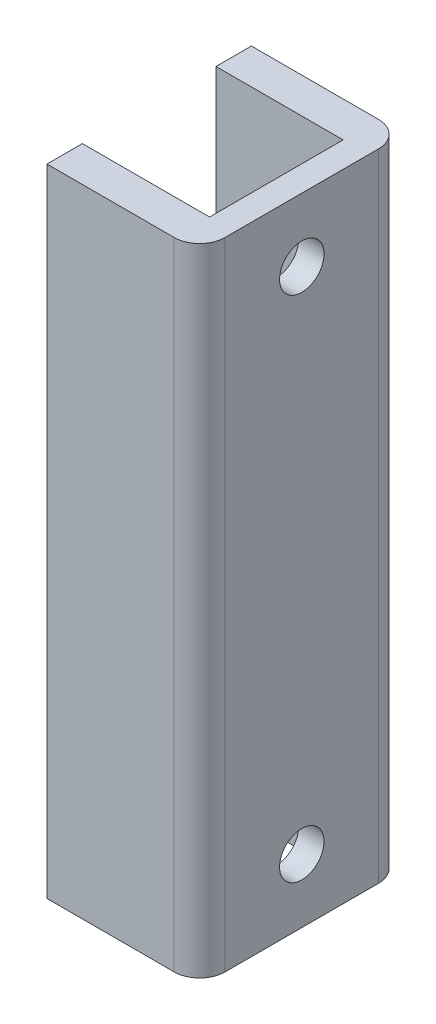
SolidWorks part; units mm, degrees
ref_plane "前视基准面" through (0, 0, 0) normal (0, 0, 1) x (1, 0, 0)
ref_plane "上视基准面" through (0, 0, 0) normal (0, 1, 0) x (1, 0, 0)
ref_plane "右视基准面" through (0, 0, 0) normal (1, 0, 0) x (0, 0, -1)
sketch "草图1" plane through (0, 0, 0) normal (0, 1, 0) x (1, 0, 0)
  line L0 (-8.0532, 9.2928) -> (1.9468, 9.2928)
  line L1 (3.9468, 7.2928) -> (3.9468, -4.7772)
  line L2 (1.9468, -6.7772) -> (-8.0532, -6.7772)
  line L3 (-8.0532, -6.7772) -> (-8.0532, -3.9922)
  line L4 (-8.0532, -3.9922) -> (1.9468, -3.9922)
  line L5 (1.9468, -3.9922) -> (1.9468, 6.5078)
  line L6 (1.9468, 6.5078) -> (-8.0532, 6.5078)
  line L7 (-8.0532, 6.5078) -> (-8.0532, 9.2928)
  arc A0 (3.9468, -4.7772) -> (1.9468, -6.7772) centre (1.9468, -4.7772) cw
  arc A1 (1.9468, 9.2928) -> (3.9468, 7.2928) centre (1.9468, 7.2928) cw
  point P10 (3.9468, -6.7772)
  point P13 (3.9468, 9.2928)
  dimension "D7" = 2
  dimension "D1" = 16.07
  dimension "D2" = 12
  dimension "D3" = 12
  dimension "D4" = 2.785
  dimension "D5" = 10.5
  dimension "D6" = 2
extrude "凸台-拉伸1" add sketch "草图1" along normal blind 50
sketch "草图2" plane through (3.9468, 0, 0) normal (1, 0, 0) x (0, 0, -1)
  line L1 (-4.7772, 50) -> (7.2928, 50) construction
  line L2 (-4.7772, 50) -> (-4.7772, 0) construction
  circle A0 centre (1.2578, 45) radius 1.75
  circle A1 centre (1.2578, 5) radius 1.75
  dimension "D1" = 3.5
  dimension "D2" = 3.5
  dimension "D3" = 40
  dimension "D4" = 5
  dimension "D5" = 6.035
extrude "切除-拉伸1" cut sketch "草图2" against normal through all
